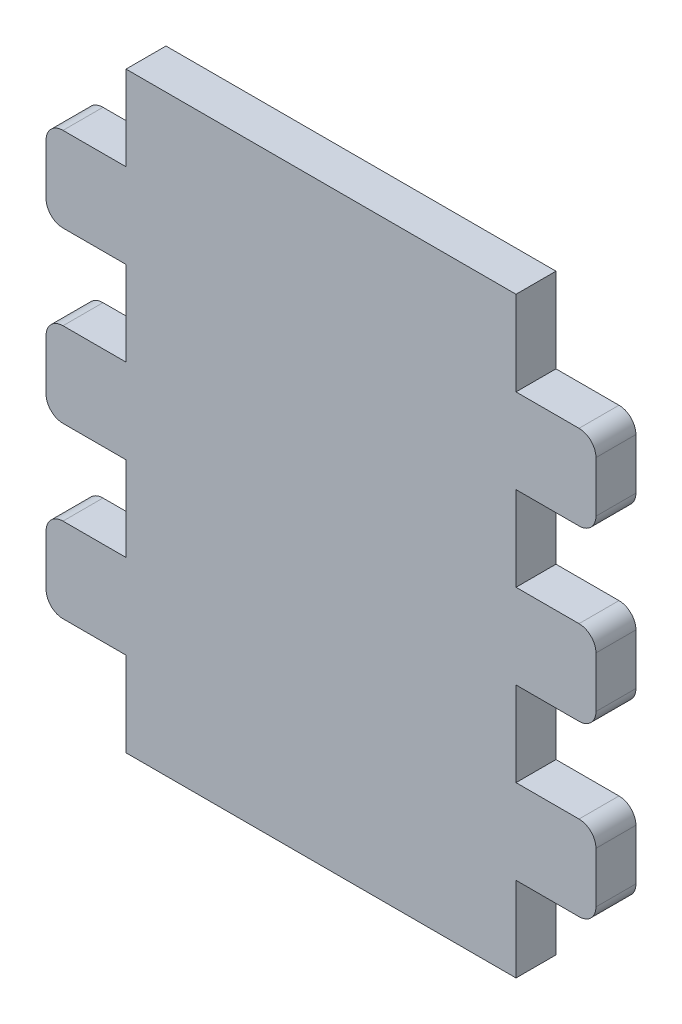
SolidWorks part; units mm, degrees
ref_plane "Front Plane" through (0, 0, 0) normal (0, 0, 1) x (1, 0, 0)
ref_plane "Top Plane" through (0, 0, 0) normal (0, 1, 0) x (1, 0, 0)
ref_plane "Right Plane" through (0, 0, 0) normal (1, 0, 0) x (0, 0, -1)
sketch "Sketch1" plane through (0, 0, 0) normal (0, 0, 1) x (1, 0, 0)
  line L1 (-14.6375, -22.225) -> (14.6375, -22.225)
  line L2 (-14.6375, -22.225) -> (-14.6375, 22.225)
  line L3 (-14.6375, 22.225) -> (14.6375, 22.225)
  line L4 (14.6375, -22.225) -> (14.6375, 22.225)
  line L5 (-14.6375, -22.225) -> (14.6375, 22.225) construction
  line L6 (-14.6375, 22.225) -> (14.6375, -22.225) construction
  point P0 (0, 0)
  dimension "D1" = 29.275
  dimension "D2" = 44.45
extrude "Boss-Extrude1" add sketch "Sketch1" along normal blind 3
sketch "Sketch2" plane through (14.6375, 0, 0) normal (1, 0, 0) x (0, 0, -1)
  line L0 (-3, -22.225) -> (-3, 22.225) construction
  line L1 (-3, -9.525) -> (0, -9.525)
  line L2 (-3, -9.525) -> (-3, -15.875)
  line L3 (-3, -15.875) -> (0, -15.875)
  line L4 (0, -9.525) -> (0, -15.875)
  line L5 (0, -22.225) -> (0, 22.225) construction
  line L6 (-3, -22.225) -> (0, -22.225) construction
  dimension "D1" = 6.35
  dimension "D2" = 6.35
extrude "Boss-Extrude2" add sketch "Sketch2" along normal blind 6
pattern_linear "LPattern1" count 3 spacing 12.7 along (0, 1, 0) of "Boss-Extrude2"
mirror "Mirror1" about plane through (0, 0, 0) normal (1, 0, 0) of "LPattern1", "Boss-Extrude2"
fillet "Fillet1" radius 1.27 12 edges at (-20.6375, 15.875, 1.5) (-20.6375, 9.525, 1.5) (-20.6375, 3.175, 1.5) (-20.6375, -3.175, 1.5) (-20.6375, -9.525, 1.5) (-20.6375, -15.875, 1.5) (20.6375, -15.875, 1.5) (20.6375, -9.525, 1.5) (20.6375, -3.175, 1.5) (20.6375, 3.175, 1.5) (20.6375, 9.525, 1.5) (20.6375, 15.875, 1.5)
